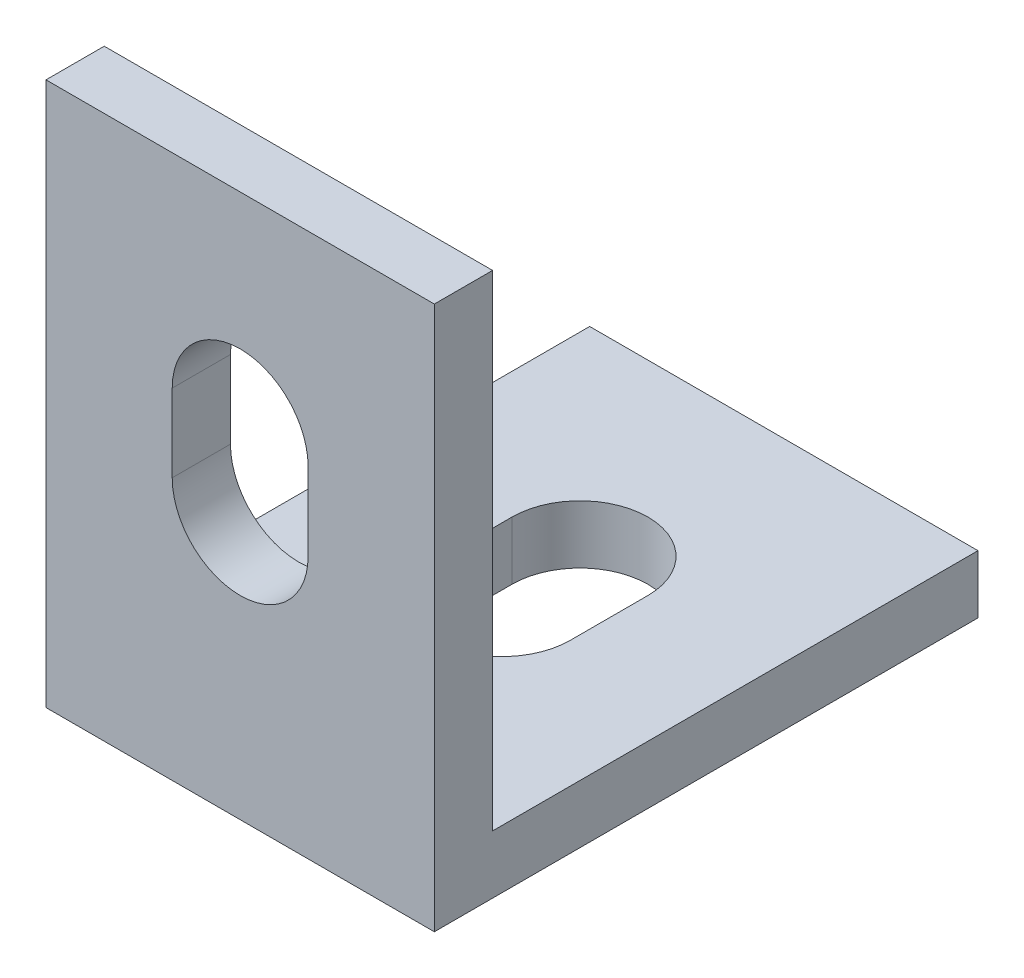
SolidWorks part; units mm, degrees
ref_plane "Front Plane" through (0, 0, 0) normal (0, 0, 1) x (1, 0, 0)
ref_plane "Top Plane" through (0, 0, 0) normal (0, 1, 0) x (1, 0, 0)
ref_plane "Right Plane" through (0, 0, 0) normal (1, 0, 0) x (0, 0, -1)
sketch "Sketch1" plane through (0, 0, 0) normal (1, 0, 0) x (0, 0, -1)
  line L0 (0, 0) -> (0, -28)
  line L1 (0, -28) -> (28, -28)
  line L2 (28, -28) -> (28, -25)
  line L6 (3, 0) -> (0, 0)
  line L7 (3, 0) -> (3, -25)
  line L8 (3, -25) -> (28, -25)
  dimension "D1" = 28
  dimension "D2" = 28
  dimension "D3" = 3
  dimension "D4" = 3
extrude "Boss-Extrude2" add sketch "Sketch1" against normal blind 20
sketch "Sketch4" plane through (0, -25, 0) normal (0, 1, 0) x (1, 0, 0)
  line L0 (-10, 3) -> (-10, 28) construction
  line L1 (-20, 3) -> (0, 3) construction
  line L2 (-20, 28) -> (0, 28) construction
  line L3 (-10, 17.5) -> (-10, 13.5) construction
  line L4 (-6.5, 17.5) -> (-6.5, 13.5)
  line L5 (-13.5, 17.5) -> (-13.5, 13.5)
  arc A0 (-6.5, 17.5) -> (-13.5, 17.5) centre (-10, 17.5) ccw
  arc A1 (-13.5, 13.5) -> (-6.5, 13.5) centre (-10, 13.5) ccw
  point P8 (-10, 15.5)
  point P13 (0, 0)
  point P14 (-10, 15.5)
  point P15 (-10, 10)
  point P16 (-10, 21)
  dimension "D1" = 11
  dimension "D2" = 7
extrude "Cut-Extrude1" cut sketch "Sketch4" against normal up to surface (3 mm away) up to face at (-10, -28, -14)
sketch "Sketch5" plane through (0, 0, -3) normal (0, 0, -1) x (-1, 0, 0)
  line L0 (10, -25) -> (10, 0) construction
  line L1 (20, -25) -> (0, -25) construction
  line L2 (20, 0) -> (0, 0) construction
  line L3 (10, -10.5) -> (10, -14.5) construction
  line L4 (13.5, -10.5) -> (13.5, -14.5)
  line L5 (6.5, -10.5) -> (6.5, -14.5)
  arc A0 (13.5, -10.5) -> (6.5, -10.5) centre (10, -10.5) ccw
  arc A1 (6.5, -14.5) -> (13.5, -14.5) centre (10, -14.5) ccw
  point P8 (10, -12.5)
  point P13 (0, 0)
  point P14 (10, -12.5)
  point P15 (10, -7)
  point P16 (10, -18)
  dimension "D1" = 11
  dimension "D2" = 7
extrude "Cut-Extrude2" cut sketch "Sketch5" against normal up to surface (3 mm away) up to face at (-10, -14, 0)
